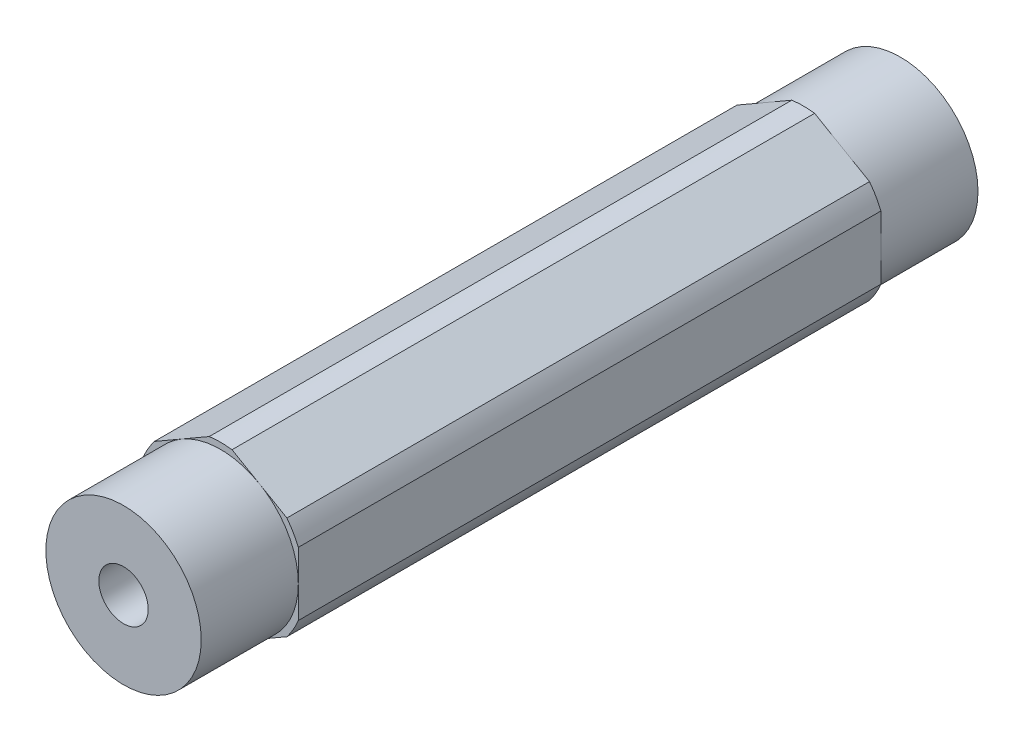
SolidWorks part; units mm, degrees
ref_plane "Front Plane" through (0, 0, 0) normal (0, 0, 1) x (1, 0, 0)
ref_plane "Top Plane" through (0, 0, 0) normal (0, 1, 0) x (1, 0, 0)
ref_plane "Right Plane" through (0, 0, 0) normal (1, 0, 0) x (0, 0, -1)
sketch "Sketch1" plane through (0, 0, 0) normal (0, 0, 1) x (1, 0, 0)
  line L1 (0, 7.3323) -> (-6.35, 3.6662)
  line L2 (-6.35, 3.6662) -> (-6.35, -3.6662)
  line L3 (-6.35, -3.6662) -> (0, -7.3323)
  line L4 (0, -7.3323) -> (6.35, -3.6662)
  line L5 (6.35, -3.6662) -> (6.35, 3.6662)
  line L6 (6.35, 3.6662) -> (0, 7.3323)
  circle A0 centre (0, 0) radius 6.35 construction
  circle A1 centre (0, 0) radius 6.858
  dimension "D1" = 12.7
  dimension "D2" = 13.716
extrude "Boss-Extrude1" add sketch "Sketch1" along normal mid plane 63.5 contours L5 A1 L6 L1 L2 L3 L4
sketch "Sketch2" plane through (0, 0, 0) normal (0, 0, 1) x (1, 0, 0)
  circle A0 centre (0, 0) radius 6.35
  dimension "D1" = 12.7
extrude "Cut-Extrude1" cut sketch "Sketch2" against normal blind 7.9375 from surface at 31.75 flip side to cut starting at face at (0, 0, 31.75)
sketch "Sketch5" plane through (0, 0, -31.75) normal (0, 0, -1) x (-1, 0, 0)
  circle A0 centre (0, 0) radius 6.35
  dimension "D1" = 12.7
extrude "Cut-Extrude5" cut sketch "Sketch5" against normal blind 7.9375 flip side to cut
hole_wizard "#10-32 Tapped Hole1" positions "3DSketch1" profile "Sketch6" tap size "#10-32" standard "ANSI Inch"
sketch3d "3DSketch1"
  line L0 (0, 0, -23.8125) -> (0, 0, -31.75) construction
  line L1 (0, 0, 23.8125) -> (0, 0, 31.75) construction
  point P0 (0, 0, -31.75)
  point P4 (0, 0, 31.75)
sketch "Sketch6" plane through (0, 0, -31.75) normal (1, 0, 0) x (0, 1, 0)
  line L0 (0, 0) -> (0, 13.2428)
  line L1 (0, 13.2428) -> (2.0193, 12.0294)
  line L2 (2.0193, 12.0294) -> (2.0193, 0)
  line L5 (2.0193, 0) -> (0, 0)
  line L10 (0, 13.2428) -> (-2.0193, 12.0294) construction
  line L11 (0, -6.35) -> (0, 107.95) construction
  dimension "Tap Drill Dia." = 4.0386
  dimension "Tap Drill Depth" = 12.0294
  dimension "Drill Angle" = 118
cosmetic thread "Hole Thread1" parameters "D1"=9.652, "D2"=4.826
cosmetic thread "Hole Thread2" parameters "D1"=9.652, "D2"=4.826
